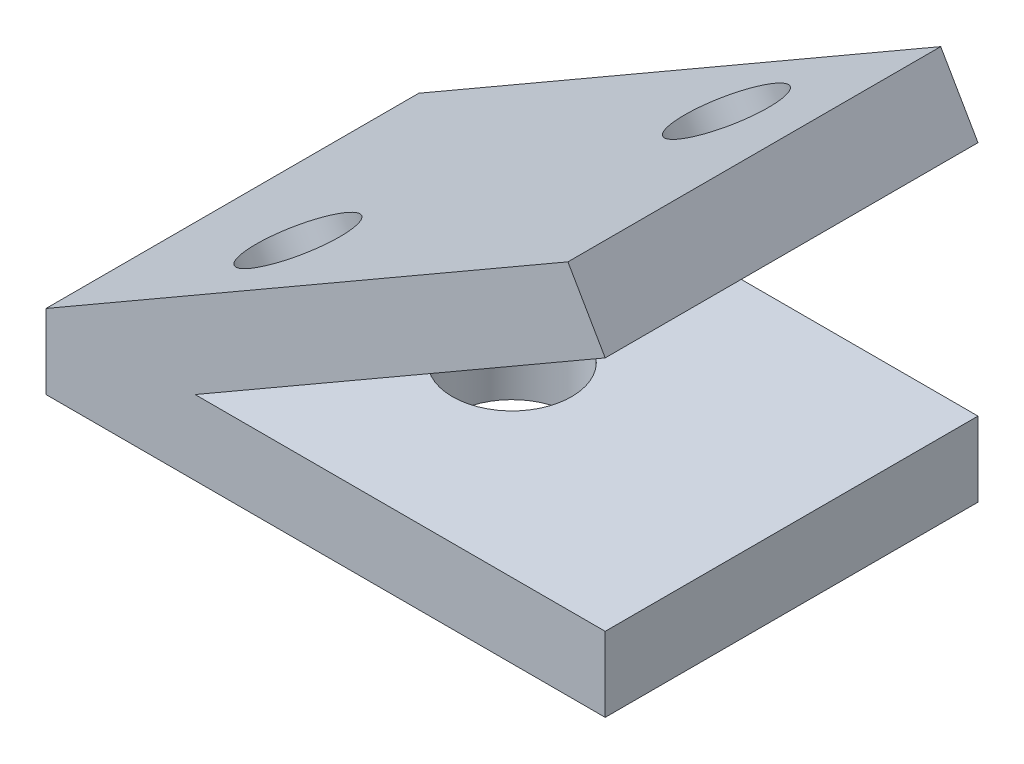
SolidWorks part; units mm, degrees
ref_plane "Front Plane" through (0, 0, 0) normal (0, 0, 1) x (1, 0, 0)
ref_plane "Top Plane" through (0, 0, 0) normal (0, 1, 0) x (1, 0, 0)
ref_plane "Right Plane" through (0, 0, 0) normal (1, 0, 0) x (0, 0, -1)
sketch "Sketch2" plane through (0, 0, 0) normal (0, 0, 1) x (1, 0, 0)
  line L1 (0, 0) -> (15, 0)
  line L2 (0, 0) -> (0, 2)
  line L3 (0, 2) -> (15, 2)
  line L4 (15, 0) -> (15, 2)
  dimension "D1" = 2
  dimension "D2" = 15
extrude "Boss-Extrude1" add sketch "Sketch2" along normal blind 10
sketch "Sketch3" plane through (0, 0, 10) normal (0, 0, 1) x (1, 0, 0)
  line L0 (0, 2) -> (4, 2)
  line L1 (15, 2) -> (0, 2) construction
  line L2 (4, 2) -> (15, 8.3509)
  line L3 (15, 8.3509) -> (14, 10.0829)
  line L4 (14, 10.0829) -> (0, 2)
  point P6 (15.219, 11.4773)
  point P8 (0, 0)
  dimension "D1" = 30
  dimension "D2" = 2
extrude "Boss-Extrude2" add sketch "Sketch3" against normal up to surface (10 mm away) up to face at (7.5, 1, 0)
sketch "Sketch4" plane through (-0.866, 1.5, 0) normal (-0.5, 0.866, 0) x (0.866, 0.5, 0)
  circle A0 centre (13.4158, -2.5) radius 1.1 construction
  circle A1 centre (5.9158, -7.5) radius 1.1 construction
  circle A2 centre (13.4158, -2.5) radius 1.1
  circle A3 centre (5.9158, -7.5) radius 1.1
  circle A4 centre (5.9158, -7.5) radius 1.3
  circle A5 centre (13.4158, -2.5) radius 1.3
  dimension "D1" = 0.2
extrude "Cut-Extrude1" cut sketch "Sketch4" against normal up to surface (2 mm away) contours A4 | A5 up to face at (9.5, 5.1754, 5)
sketch "Sketch5" plane through (0, 2, 0) normal (0, 1, 0) x (1, 0, 0)
  line L0 (0, 0) -> (15, -10) construction
  line L1 (15, -10) -> (0, -10) construction
  line L2 (0, -10) -> (15, 0) construction
  circle A0 centre (7.5, -5) radius 1.6
  dimension "D1" = 3.2
extrude "Cut-Extrude2" cut sketch "Sketch5" against normal up to surface (2 mm away) up to face at (7.5, 0, 5)
equation "\"a\"= 30deg"
equation "\"D1@Sketch3\"=\"a\""
